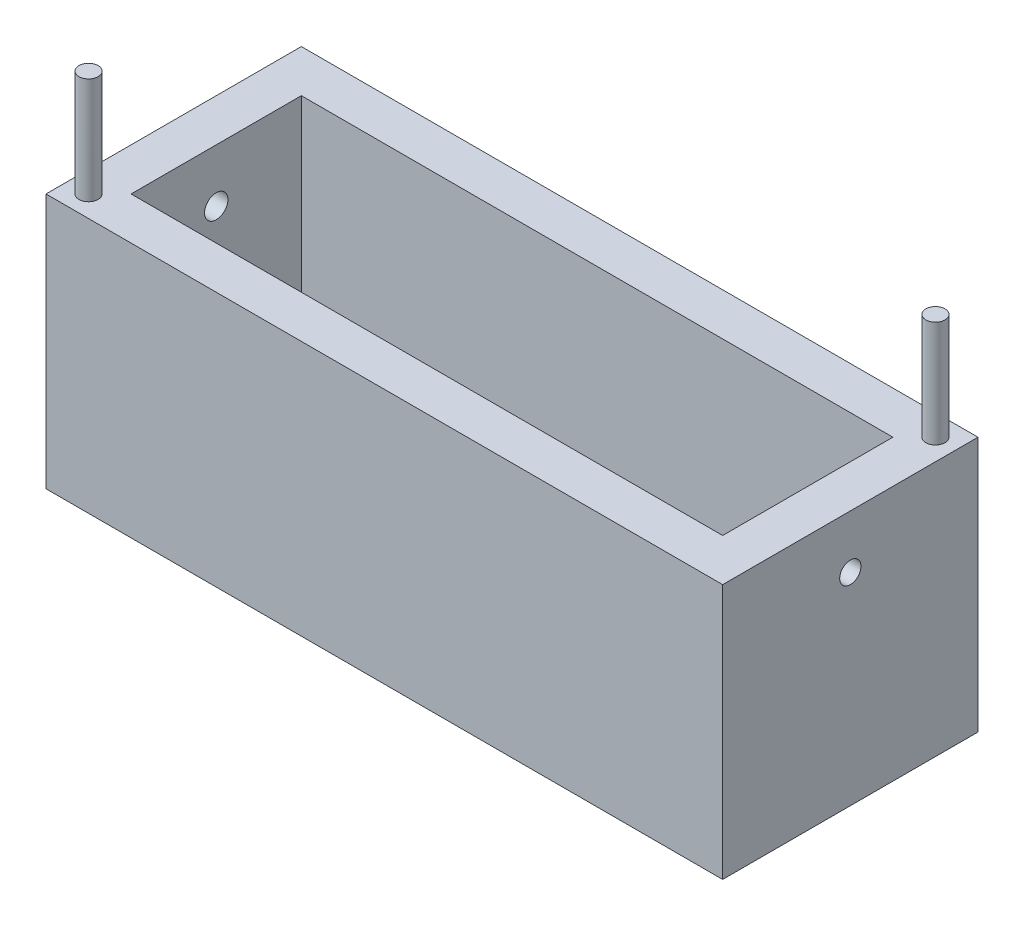
SolidWorks part; units mm, degrees
ref_plane "Front Plane" through (0, 0, 0) normal (0, 0, 1) x (1, 0, 0)
ref_plane "Top Plane" through (0, 0, 0) normal (0, 1, 0) x (1, 0, 0)
ref_plane "Right Plane" through (0, 0, 0) normal (1, 0, 0) x (0, 0, -1)
sketch "Sketch1" plane through (0, 0, 0) normal (0, 1, 0) x (1, 0, 0)
  line L1 (0, 0) -> (403.86, 0)
  line L2 (0, 0) -> (0, 152.4)
  line L3 (0, 152.4) -> (403.86, 152.4)
  line L4 (403.86, 0) -> (403.86, 152.4)
  dimension "D1" = 403.86
  dimension "D2" = 152.4
extrude "Boss-Extrude1" add sketch "Sketch1" against normal blind 152.4
sketch "Sketch2" plane through (0, 0, 0) normal (0, 1, 0) x (1, 0, 0)
  line L0 (0, 152.4) -> (0, 0) construction
  line L1 (25.4, 25.4) -> (378.46, 25.4)
  line L2 (25.4, 25.4) -> (25.4, 127)
  line L3 (25.4, 127) -> (378.46, 127)
  line L4 (378.46, 25.4) -> (378.46, 127)
  line L5 (0, 0) -> (403.86, 0) construction
  dimension "D1" = 353.06
  dimension "D2" = 25.4
  dimension "D3" = 25.4
  dimension "D4" = 101.6
extrude "Cut-Extrude1" cut sketch "Sketch2" against normal blind 139.7
sketch "Sketch5" plane through (0, 0, 0) normal (0, 1, 0) x (1, 0, 0)
  line L3 (25.4, 25.4) -> (378.46, 25.4) construction
  line L6 (0, 152.4) -> (0, 0) construction
  circle A0 centre (12.7, 12.7) radius 5.715
  dimension "D1" = 12.7
  dimension "D2" = 12.7
extrude "Boss-Extrude2" add sketch "Sketch5" along normal blind 63.5
sketch "Sketch6" plane through (0, 0, 0) normal (0, 1, 0) x (1, 0, 0)
  line L0 (403.86, 0) -> (403.86, 152.4) construction
  line L1 (403.86, 152.4) -> (0, 152.4) construction
  circle A0 centre (391.16, 139.7) radius 5.715
  point P2 (0, 0)
  point P8 (391.16, 139.7)
  dimension "D1" = 12.7
  dimension "D3" = 11.43
  dimension "D2" = 12.7
extrude "Boss-Extrude3" add sketch "Sketch6" along normal blind 63.5
sketch "Sketch7" plane through (403.86, 0, 0) normal (1, 0, 0) x (0, 0, -1)
  line L0 (0, 0) -> (152.4, 0) construction
  line L1 (0, -152.4) -> (0, 0) construction
  circle A0 centre (76.2, -31.75) radius 6.35
  dimension "D1" = 31.75
  dimension "D2" = 76.2
extrude "Cut-Extrude4" cut sketch "Sketch7" against normal blind 63.5 contours A0
sketch "Sketch8" plane through (0, 0, 0) normal (-1, 0, 0) x (0, 0, 1)
  line L0 (-152.4, 0) -> (0, 0) construction
  line L1 (-152.4, -152.4) -> (-152.4, 0) construction
  circle A0 centre (-76.2, -31.75) radius 6.985
  dimension "D1" = 31.75
  dimension "D2" = 76.2
extrude "Cut-Extrude5" cut sketch "Sketch8" against normal blind 63.5
